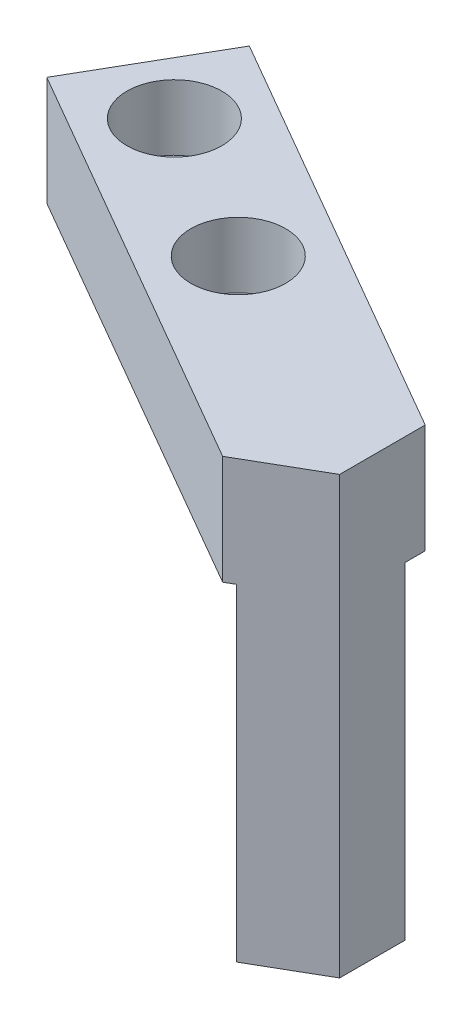
SolidWorks part; units mm, degrees
ref_plane "前基準面" through (0, 0, 0) normal (0, 0, 1) x (1, 0, 0)
ref_plane "上基準面" through (0, 0, 0) normal (0, 1, 0) x (1, 0, 0)
ref_plane "右基準面" through (0, 0, 0) normal (1, 0, 0) x (0, 0, -1)
ref_plane "平面1" through (0, -5, 0) normal (0, -1, 0) x (1, 0, 0)
sketch "草圖1" plane through (0, -5, 0) normal (0, -1, 0) x (1, 0, 0)
  line L0 (0, -3.926) -> (0, 0)
  line L1 (0, 0) -> (-3.4, 1.963)
  line L2 (-3.4, 1.963) -> (-22.4846, -9.0555)
  line L3 (-22.4846, -9.0555) -> (-19.0846, -14.9445)
  line L4 (-19.0846, -14.9445) -> (0, -3.926)
extrude "填料-伸長1" add sketch "草圖1" against normal blind 5
sketch "草圖2" plane through (0, -5, 0) normal (0, -1, 0) x (1, 0, 0)
  line L0 (0, -2.9979) -> (-3, -2.9979)
  line L1 (-3, -2.9979) -> (-3, 1.7321)
  line L2 (-3, 1.7321) -> (0, 0)
  line L3 (0, 0) -> (0, -2.9979)
extrude "填料-伸長2" add sketch "草圖2" along normal blind 15
hole_wizard "M2 六角頭機械螺釘的柱孔1" positions "草圖4" profile "草圖3" counterbore size "M2" standard "Ansi Metric"
sketch "草圖4" plane through (0, 0, 0) normal (0, 1, 0) x (1, 0, 0)
  point P0 (-10.9985, 6.35)
  point P1 (-17.9267, 10.35)
sketch "草圖3" plane through (-10.9985, 0, -6.35) normal (1, 0, 0) x (0, 0, 1)
  line L0 (0, 0) -> (0, 20)
  line L1 (0, 20) -> (1.175, 20)
  line L3 (1.175, 20) -> (1.175, 3)
  line L4 (1.175, 3) -> (2.175, 3)
  line L5 (2.175, 3) -> (2.175, 0)
  line L7 (2.175, 0) -> (0, 0)
  line L11 (0, -6.35) -> (0, 107.95) construction
  dimension "貫穿孔直徑" = 2.35
  dimension "貫穿孔深度" = 20
  dimension "柱孔直徑" = 4.35
  dimension "柱孔深度" = 3
